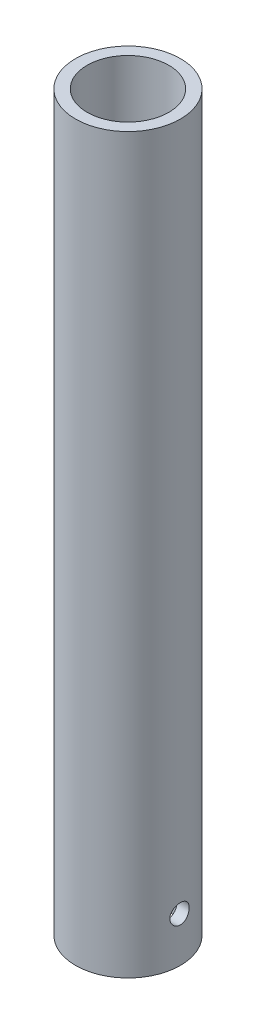
SolidWorks part; units mm, degrees
ref_plane "Front Plane" through (0, 0, 0) normal (0, 0, 1) x (1, 0, 0)
ref_plane "Top Plane" through (0, 0, 0) normal (0, 1, 0) x (1, 0, 0)
ref_plane "Right Plane" through (0, 0, 0) normal (1, 0, 0) x (0, 0, -1)
sketch "Sketch1" plane through (0, 0, 0) normal (0, 1, 0) x (1, 0, 0)
  circle A0 centre (0, 0) radius 10.85
  circle A1 centre (0, 0) radius 8.45
extrude "Boss-Extrude1" add sketch "Sketch1" along normal blind 151.72
sketch "Sketch3" plane through (0, 0, 0) normal (0, 0, 1) x (1, 0, 0)
  line L0 (-10.85, 0) -> (10.85, 0) construction
  circle A0 centre (0, 9.28) radius 2
  dimension "D1" = 9.28
extrude "Cut-Extrude2" cut sketch "Sketch3" against normal through all
sketch "Sketch4" plane through (0, 0, 0) normal (1, 0, 0) x (0, 0, -1)
  line L0 (-10.85, 0) -> (10.85, 0) construction
  circle A0 centre (0, 9.28) radius 2
  dimension "D1" = 9.28
extrude "Cut-Extrude3" cut sketch "Sketch4" against normal through all and the other way through all
